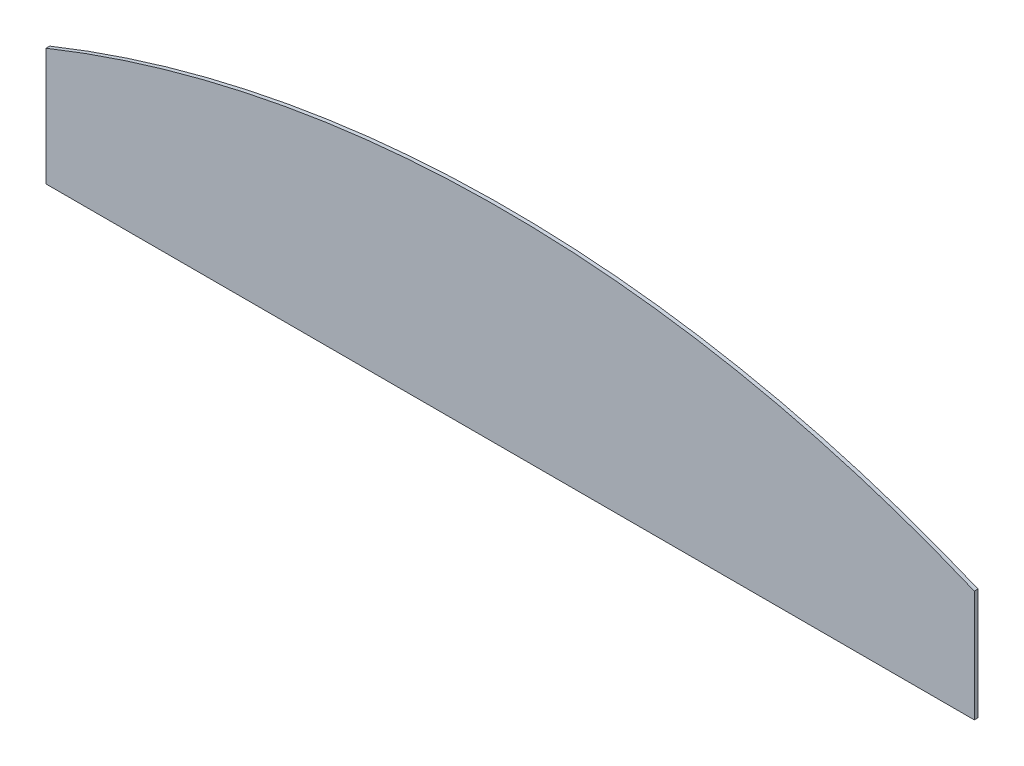
SolidWorks part; units mm, degrees
material "ASTM A36 Steel"
ref_plane "Front Plane" through (0, 0, 0) normal (0, 0, 1) x (1, 0, 0)
ref_plane "Top Plane" through (0, 0, 0) normal (0, 1, 0) x (1, 0, 0)
ref_plane "Right Plane" through (0, 0, 0) normal (1, 0, 0) x (0, 0, -1)
sketch "Sketch1" plane through (0, 0, 0) normal (0, 0, 1) x (1, 0, 0)
  line L1 (-187.0079, 415.5806) -> (192.9921, 415.5806)
  line L2 (-187.0079, 415.5806) -> (-187.0079, 463.7112)
  line L3 (192.9921, 415.5806) -> (192.9921, 461.2527)
  arc A0 (192.9921, 461.2527) -> (-187.0079, 463.7112) centre (0, 0) ccw
  dimension "D1" = 1000
  dimension "D3" = 380
extrude "Boss-Extrude1" add sketch "Sketch1" along normal blind 1.5
